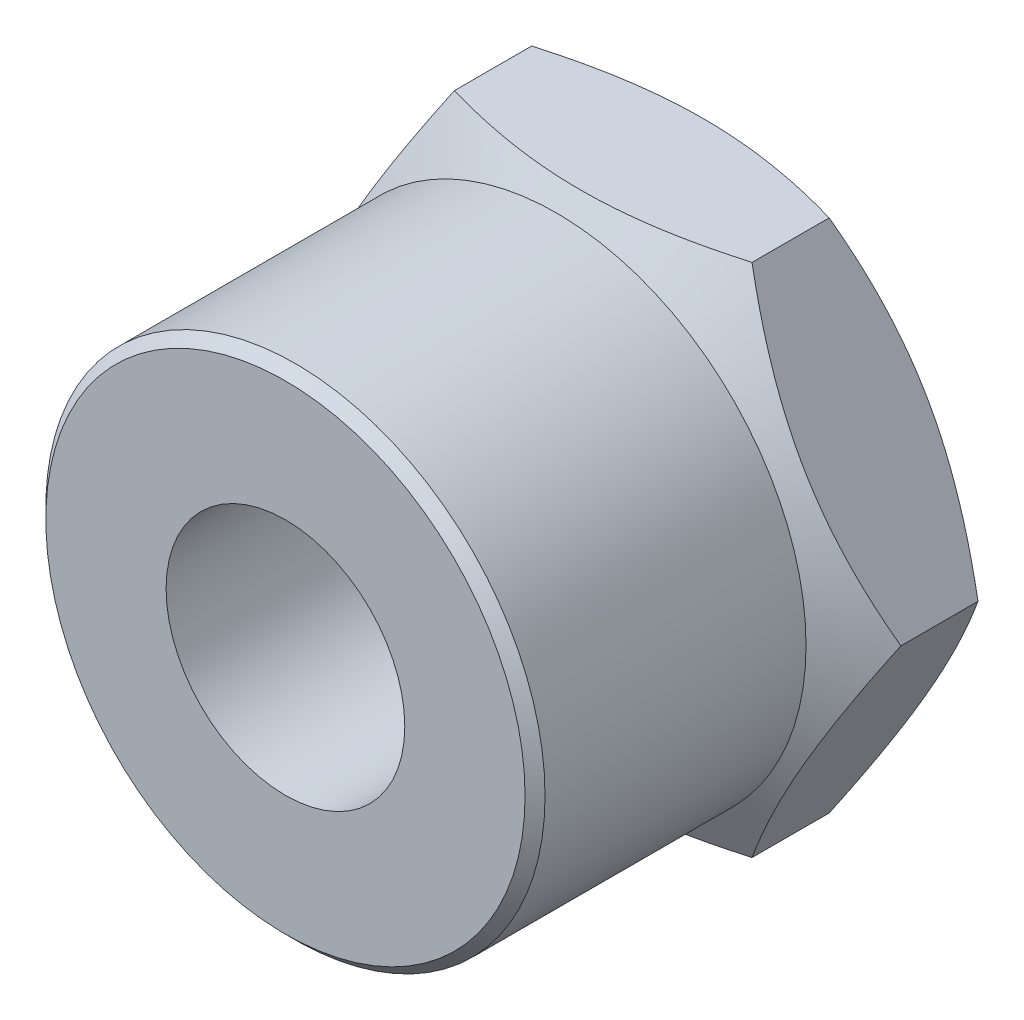
SolidWorks part; units mm, degrees
ref_plane "Front" through (0, 0, 0) normal (0, 0, 1) x (1, 0, 0)
ref_plane "Top" through (0, 0, 0) normal (0, 1, 0) x (1, 0, 0)
ref_plane "Right" through (0, 0, 0) normal (1, 0, 0) x (0, 0, -1)
sketch "Sketch1" plane through (0, 0, 0) normal (0, 0, 1) x (1, 0, 0)
  line L1 (2.0207, -3.5) -> (4.0415, 0)
  line L2 (4.0415, 0) -> (2.0207, 3.5)
  line L3 (2.0207, 3.5) -> (-2.0207, 3.5)
  line L4 (-2.0207, 3.5) -> (-4.0415, 0)
  line L5 (-4.0415, 0) -> (-2.0207, -3.5)
  line L6 (-2.0207, -3.5) -> (2.0207, -3.5)
  circle A0 centre (0, 0) radius 3.5 construction
  circle A1 centre (0, 0) radius 1.621
  dimension "xd" = 3.242
  dimension "s" = 7
extrude "BaseNut" add sketch "Sketch1" against normal blind 2.32
cosmetic thread "ThreadCosmetic1" [suppressed] parameters "m"=2.9, "D2"=4
sketch "Sketch3" plane through (0, 0, 0) normal (0, 1, 0) x (1, 0, 0)
  line L0 (0, 16.3108) -> (0, -16.1137) construction
  line L2 (-2.0696, 1.16) -> (33.5085, 1.16) construction
  line L3 (2.94, 2.32) -> (4.0415, 2.32)
  line L5 (4.0415, 2.32) -> (4.0415, 1.6841)
  line L7 (4.0415, 1.6841) -> (2.94, 2.32)
  line L8 (4.0415, 0.6359) -> (2.94, 0)
  line L9 (4.0415, 0) -> (4.0415, 0.6359)
  line L10 (2.94, 0) -> (4.0415, 0)
  dimension "D1" = 30
  dimension "dw" = 5.88
revolve "Double-Chamfer" cut sketch "Sketch3" angle 360 about L0
sketch "Sketch2" plane through (20.0871, -4.2815, 0) normal (0, 0, 1) x (1, 0, 0)
  circle A1 centre (-20.0871, 4.2815) radius 1.621 construction
  circle A2 centre (-20.0871, 4.2815) radius 3.39
  circle A3 centre (-20.0871, 4.2815) radius 1.621
  dimension "s1" = 6.78
extrude "Extrude1" add sketch "Sketch2" along normal offset from surface (3.68 mm away) 6 up to face at (1.621, 0, -2.32)
sketch "Sketch5" plane through (0, 0, 0) normal (0, 1, 0) x (1, 0, 0)
  line L0 (0, 16.8008) -> (0, -2.8116) construction
  line L2 (1.621, 2.32) -> (2.3, 2.32)
  line L5 (2.3, 2.32) -> (1.621, 1.641)
  line L7 (1.621, 1.641) -> (1.621, 2.32)
  dimension "D1" = 45
  dimension "da" = 4.6
revolve "EndChamfer" cut sketch "Sketch5" angle 360 about L0
chamfer "Chamfer1" distance 0.1356 angle 45 1 edges at (3.39, 0, 3.68)
sketch "Sketch6" plane through (0, 0, 0) normal (0, 1, 0) x (1, 0, 0)
  line L0 (0, 30.0005) -> (0, -32.7386) construction
  line L1 (1.242, 1.8305) -> (1.621, 1.8305)
  line L2 (1.621, 1.8305) -> (1.9492, 1.641)
  line L3 (1.9492, 1.641) -> (1.621, 1.4515)
  line L4 (1.621, 1.4515) -> (1.242, 1.4515)
  line L5 (1.242, 1.4515) -> (1.242, 1.8305)
  line L6 (-1.621, 1.641) -> (1.621, 1.641) construction
  dimension "D1" = 0.379
  dimension "D2" = 3.242
revolve "Cut-Revolve10" [suppressed] cut sketch "Sketch6" angle 360 about L0
pattern_linear "LPattern10" [suppressed] count 5 spacing 0.4548 along (0, 0, 1)
equation "\"D1@Chamfer1\" = \"s1@Sketch2\" / 50"
equation "\"D2@Sketch6\" = \"xd@Sketch1\""
equation "\"D1@Sketch6\" = (  \"D2@ThreadCosmetic1\" - \"xd@Sketch1\" )  / 2"
equation "\"D3@LPattern10\" = \"D1@Sketch6\" * 1.2"
equation "\"D1@LPattern10\" = \"m1@BaseNut\" / \"D3@LPattern10\""
